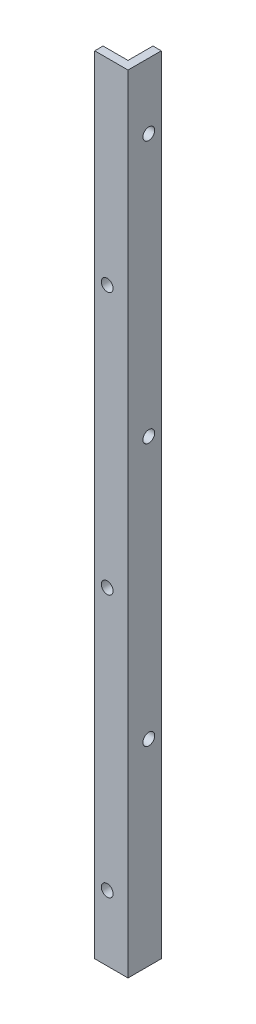
SolidWorks part; units mm, degrees
material "Alumina"
ref_plane "Front Plane" through (0, 0, 0) normal (0, 0, 1) x (1, 0, 0)
ref_plane "Top Plane" through (0, 0, 0) normal (0, 1, 0) x (1, 0, 0)
ref_plane "Right Plane" through (0, 0, 0) normal (1, 0, 0) x (0, 0, -1)
sketch "Sketch1" plane through (0, 0, 0) normal (0, 1, 0) x (1, 0, 0)
  line L0 (0, 0) -> (0, 12.7)
  line L1 (0, 0) -> (-12.7, 0)
  line L2 (-3.18, 3.18) -> (-3.18, 12.7)
  line L3 (-3.18, 3.18) -> (-12.7, 3.18)
  line L4 (-3.18, 12.7) -> (0, 12.7)
  line L5 (-12.7, 3.18) -> (-12.7, -0.2944)
  dimension "D1" = 12.7
  dimension "D2" = 12.7
  dimension "D3" = 3.18
extrude "Boss-Extrude1" add sketch "Sketch1" along normal blind 300 contours L3 L5 L1 L0 L4 L2
sketch "Sketch2" plane through (-3.18, 0, 0) normal (-1, 0, 0) x (0, 0, 1)
  line L0 (-7.94, 300) -> (-7.94, 0) construction
  line L1 (-3.18, 300) -> (-12.7, 300) construction
  line L2 (-3.18, 0) -> (-12.7, 0) construction
  circle A0 centre (-7.94, 275) radius 2.25
  circle A1 centre (-7.94, 175) radius 2.25
  circle A2 centre (-7.94, 75) radius 2.25
  dimension "D1" = 4.5
  dimension "D2" = 25
extrude "Cut-Extrude1" cut sketch "Sketch2" against normal blind 10
sketch "Sketch3" plane through (0, 0, -3.18) normal (0, 0, -1) x (-1, 0, 0)
  line L0 (7.94, 300) -> (7.94, 0) construction
  line L1 (3.18, 300) -> (12.7, 300) construction
  line L2 (3.18, 0) -> (12.7, 0) construction
  circle A0 centre (7.94, 225) radius 2.25
  circle A1 centre (7.94, 125) radius 2.25
  circle A2 centre (7.94, 25) radius 2.25
  dimension "D1" = 4.5
  dimension "D2" = 75
extrude "Cut-Extrude2" cut sketch "Sketch3" against normal blind 10
